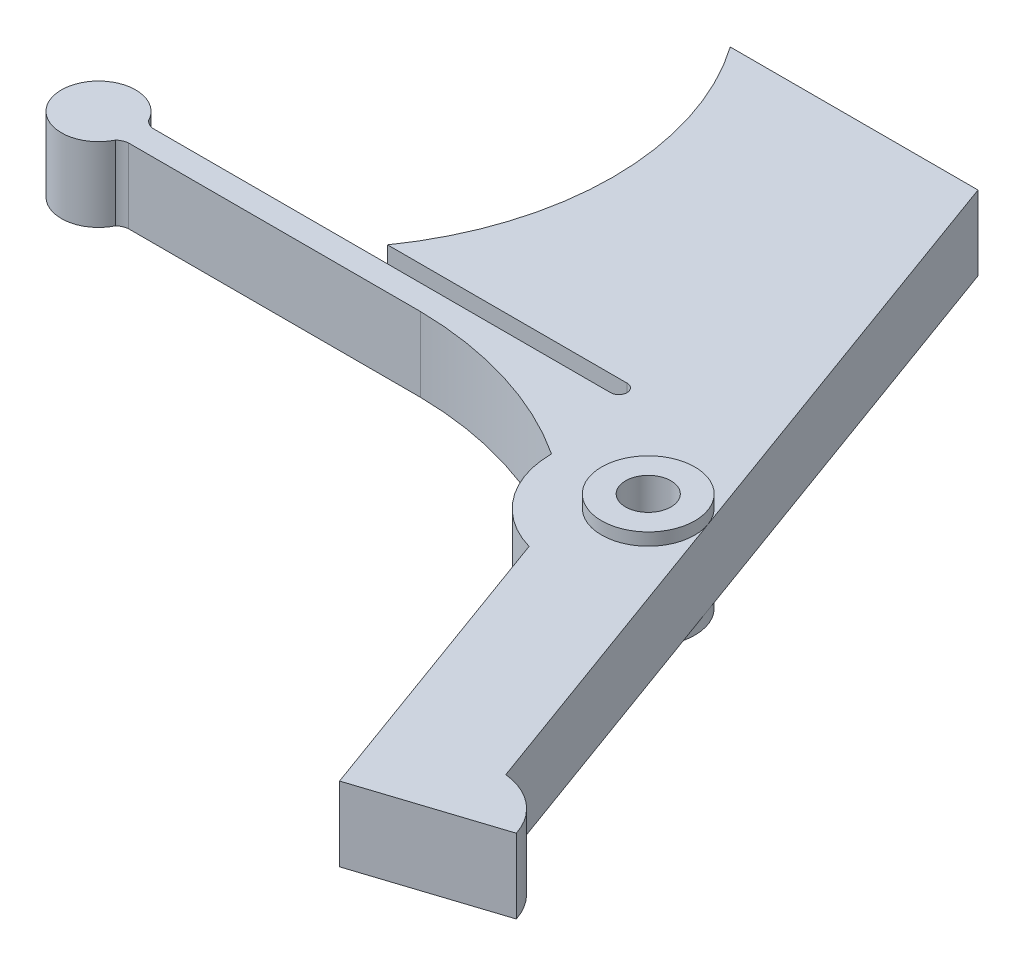
SolidWorks part; units mm, degrees
material "ABS"
ref_plane "Front Plane" through (0, 0, 0) normal (0, 0, 1) x (1, 0, 0)
ref_plane "Top Plane" through (0, 0, 0) normal (0, 1, 0) x (1, 0, 0)
ref_plane "Right Plane" through (0, 0, 0) normal (1, 0, 0) x (0, 0, -1)
sketch "Sketch1" plane through (0, 0, 0) normal (0, 1, 0) x (1, 0, 0)
  line L0 (0, 23.9452) -> (0, 8.4096) construction
  line L1 (0, 23.9452) -> (16.6219, -21.7231)
  line L5 (-15.24, 23.9452) -> (0, 23.9452)
  line L6 (-0.508, 1.8472) -> (-28.6791, 1.8472)
  line L10 (11.8501, -27.1788) -> (5.179, -8.8502)
  line L14 (-0.508, 2.8632) -> (-15.24, 2.8632)
  line L15 (11.8501, -27.1788) -> (20.0669, -24.5211)
  line L19 (-28.6504, 0.3232) -> (-10.668, 0.3232)
  arc A2 (-15.24, 2.8632) -> (-15.24, 23.9452) centre (-30.2729, 13.4042) ccw
  arc A3 (0.9415, -3.2328) -> (5.179, -8.8502) centre (6.7835, -3.2328) ccw
  arc A4 (0.9415, -3.2328) -> (-10.668, 0.3232) centre (-10.9568, -21.3489) ccw
  arc A6 (-0.508, 1.8472) -> (-0.508, 2.8632) centre (-0.508, 2.3552) ccw
  arc A7 (-29.2064, 2.1254) -> (-29.1919, 0.0738) centre (-31.242, 1.0852) ccw
  arc A8 (-29.1919, 0.0738) -> (-28.6504, 0.3232) centre (-28.5417, -0.6254) cw
  arc A9 (-28.6791, 1.8472) -> (-29.2064, 2.1254) centre (-28.5194, 2.7886) cw
  arc A10 (20.0669, -24.5211) -> (16.6219, -21.7231) centre (16.1897, -25.7751) ccw
  dimension "D5" = 21.082
  dimension "D16" = 11.684
  dimension "D22" = 1.016
  dimension "D24" = 4.572
  dimension "D3" = 8.636
  dimension "D8" = 20
  dimension "D15" = 6.35
extrude "Boss-Extrude1" add sketch "Sketch1" along normal blind 4.572
sketch "Sketch2" plane through (0, 4.572, 0) normal (0, 1, 0) x (1, 0, 0)
  circle A1 centre (6.8077, -3.1481) radius 2.8693
extrude "Boss-Extrude2" add sketch "Sketch2" along normal blind 0.762 and the other way blind 5.334 contours A1
sketch "Sketch3" plane through (0, 5.334, 0) normal (0, 1, 0) x (1, 0, 0)
  circle A0 centre (9.6173, -2.1255) radius 0.1206
  circle A1 centre (6.8077, -3.1481) radius 1.397
  circle A3 centre (6.8077, -3.1481) radius 2.8693
  dimension "D1" = 2.794
extrude "Cut-Extrude1" cut sketch "Sketch3" against normal through all contours A1
